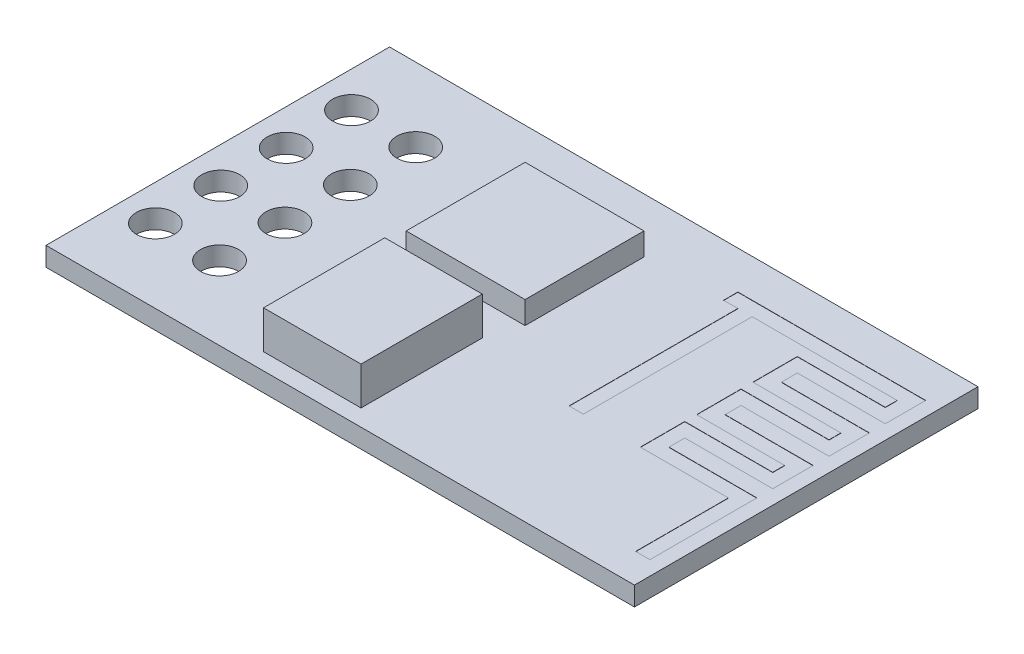
SolidWorks part; units mm, degrees
ref_plane "Plan de face" through (0, 0, 0) normal (0, 0, 1) x (1, 0, 0)
ref_plane "Plan de dessus" through (0, 0, 0) normal (0, 1, 0) x (1, 0, 0)
ref_plane "Plan de droite" through (0, 0, 0) normal (1, 0, 0) x (0, 0, -1)
sketch "Esquisse1" plane through (0, 0, 0) normal (0, 1, 0) x (1, 0, 0)
  line L1 (-12.375, -7.225) -> (12.375, -7.225)
  line L2 (-12.375, -7.225) -> (-12.375, 7.225)
  line L3 (-12.375, 7.225) -> (12.375, 7.225)
  line L4 (12.375, -7.225) -> (12.375, 7.225)
  line L5 (-12.375, -7.225) -> (12.375, 7.225) construction
  line L6 (-12.375, 7.225) -> (12.375, -7.225) construction
  point P0 (0, 0)
  dimension "D1" = 14.45
  dimension "D2" = 24.75
extrude "Boss.-Extru.1" add sketch "Esquisse1" along normal blind 0.8
sketch "Esquisse2" plane through (0, 0.8, 0) normal (0, 1, 0) x (1, 0, 0)
  line L0 (12.375, 7.225) -> (-12.375, 7.225) construction
  line L7 (-4.375, -0.075) -> (0.625, -0.075)
  line L8 (-4.375, -0.075) -> (-4.375, 4.925)
  line L9 (-4.375, 4.925) -> (0.625, 4.925)
  line L10 (0.625, -0.075) -> (0.625, 4.925)
  line L11 (-4.375, -0.075) -> (0.625, 4.925) construction
  line L12 (-4.375, 4.925) -> (0.625, -0.075) construction
  line L13 (-12.375, 7.225) -> (-12.375, -7.225) construction
  point P5 (-1.875, 2.425)
  dimension "D1" = 5
  dimension "D2" = 5
  dimension "D3" = 2.3
  dimension "D4" = 8
extrude "Boss.-Extru.2" add sketch "Esquisse2" along normal blind 0.95 contours L8 L9 L10 L7
sketch "Esquisse4" plane through (0, 0.8, 0) normal (0, 1, 0) x (1, 0, 0)
  line L0 (-4.375, -0.075) -> (0.625, -0.075) construction
  line L1 (-3.925, -6.525) -> (0.175, -6.525)
  line L2 (-3.925, -6.525) -> (-3.925, -1.425)
  line L3 (-3.925, -1.425) -> (0.175, -1.425)
  line L4 (0.175, -6.525) -> (0.175, -1.425)
  line L5 (-3.925, -6.525) -> (0.175, -1.425) construction
  line L6 (-3.925, -1.425) -> (0.175, -6.525) construction
  line L7 (-12.375, -7.225) -> (12.375, -7.225) construction
  point P0 (-1.875, -3.975)
  point P5 (-1.875, -1.425)
  point P8 (-1.875, -0.075)
  dimension "D1" = 5.1
  dimension "D2" = 4.1
  dimension "D3" = 0.7
extrude "Boss.-Extru.3" add sketch "Esquisse4" along normal blind 1.6
sketch "Esquisse5" plane through (0, 0.8, 0) normal (0, 1, 0) x (1, 0, 0)
  line L1 (-12.375, 7.225) -> (-12.375, -7.225) construction
  line L2 (-12.375, -7.225) -> (12.375, -7.225) construction
  circle A0 centre (-10.875, -4.125) radius 0.8
  circle A1 centre (-10.875, -1.375) radius 0.8
  circle A2 centre (-10.875, 1.375) radius 0.8
  circle A3 centre (-10.875, 4.125) radius 0.8
  circle A4 centre (-8.175, 4.125) radius 0.8
  circle A5 centre (-8.175, 1.375) radius 0.8
  circle A6 centre (-8.175, -1.375) radius 0.8
  circle A7 centre (-8.175, -4.125) radius 0.8
  point P4 (-11.675, -4.125)
  point P5 (-10.875, -4.925)
  point P8 (-10.875, 4.925)
  point P9 (-10.875, 4.925)
  dimension "D1" = 1.6
  dimension "D2" = 0.7
  dimension "D3" = 2.3
  dimension "D5" = 2.75
  dimension "D7" = 2.7
  dimension "D4" = 4
  dimension "D6" = 2
extrude "Enlèv. mat.-Extru.1" cut sketch "Esquisse5" against normal blind 1.6
sketch "Esquisse6" plane through (0, 0.8, 0) normal (0, 1, 0) x (1, 0, 0)
  line L0 (3.875, 5.625) -> (11.775, 5.625)
  line L1 (11.775, 5.625) -> (11.775, 3.925)
  line L2 (11.775, 3.925) -> (8.075, 3.925)
  line L3 (8.075, 3.925) -> (8.075, 3.2583)
  line L4 (8.075, 3.2583) -> (11.775, 3.2583)
  line L5 (11.775, 3.2583) -> (11.775, 1.5583)
  line L6 (11.775, 1.5583) -> (8.075, 1.5583)
  line L7 (8.075, 1.5583) -> (8.075, 0.8917)
  line L8 (8.075, 0.8917) -> (11.775, 0.8917)
  line L9 (11.775, 0.8917) -> (11.775, -0.8083)
  line L10 (11.775, -0.8083) -> (8.075, -0.8083)
  line L11 (8.075, -0.8083) -> (8.075, -1.475)
  line L12 (8.075, -1.475) -> (11.775, -1.475)
  line L13 (11.775, -1.475) -> (11.775, -5.975)
  line L14 (11.775, -5.975) -> (11.175, -5.975)
  line L15 (11.175, -5.975) -> (11.175, -2.075)
  line L16 (11.175, -2.075) -> (7.475, -2.075)
  line L17 (7.475, -2.075) -> (7.475, -0.2083)
  line L18 (7.475, -0.2083) -> (11.175, -0.2083)
  line L19 (11.175, -0.2083) -> (11.175, 0.2917)
  line L20 (11.175, 0.2917) -> (7.475, 0.2917)
  line L21 (7.475, 0.2917) -> (7.475, 2.1583)
  line L22 (7.475, 2.1583) -> (11.175, 2.1583)
  line L23 (11.175, 2.1583) -> (11.175, 2.6583)
  line L24 (11.175, 2.6583) -> (7.475, 2.6583)
  line L25 (7.475, 2.6583) -> (7.475, 4.525)
  line L26 (7.475, 4.525) -> (11.175, 4.525)
  line L27 (11.175, 4.525) -> (11.175, 5.025)
  line L28 (11.175, 5.025) -> (5.075, 5.025)
  line L29 (5.075, 5.025) -> (5.075, -2.075)
  line L30 (5.075, -2.075) -> (4.475, -2.075)
  line L31 (4.475, -2.075) -> (4.475, 5.025)
  line L32 (4.475, 5.025) -> (3.875, 5.025)
  line L33 (3.875, 5.025) -> (3.875, 5.625)
  line L34 (12.375, 7.225) -> (-12.375, 7.225) construction
  line L35 (12.375, -7.225) -> (12.375, 7.225) construction
  point P33 (11.775, 2.4083)
  point P35 (11.775, 0.0417)
  dimension "D1" = 0.6
  dimension "D2" = 0.6
  dimension "D3" = 0.6
  dimension "D4" = 0.6
  dimension "D5" = 0.6
  dimension "D6" = 0.6
  dimension "D7" = 0.6
  dimension "D8" = 0.6
  dimension "D9" = 0.6
  dimension "D10" = 0.6
  dimension "D11" = 0.6
  dimension "D12" = 0.6
  dimension "D13" = 0.6
  dimension "D14" = 1.7
  dimension "D15" = 1.7
  dimension "D16" = 1.7
  dimension "D17" = 7.7
  dimension "D18" = 0.6
  dimension "D19" = 4.5
  dimension "D20" = 4.3
  dimension "D21" = 1.6
  dimension "D22" = 0.6
  dimension "D23" = 0.6
  dimension "D24" = 7.9
extrude "Enlèv. mat.-Extru.2" cut sketch "Esquisse6" against normal blind 0.01
